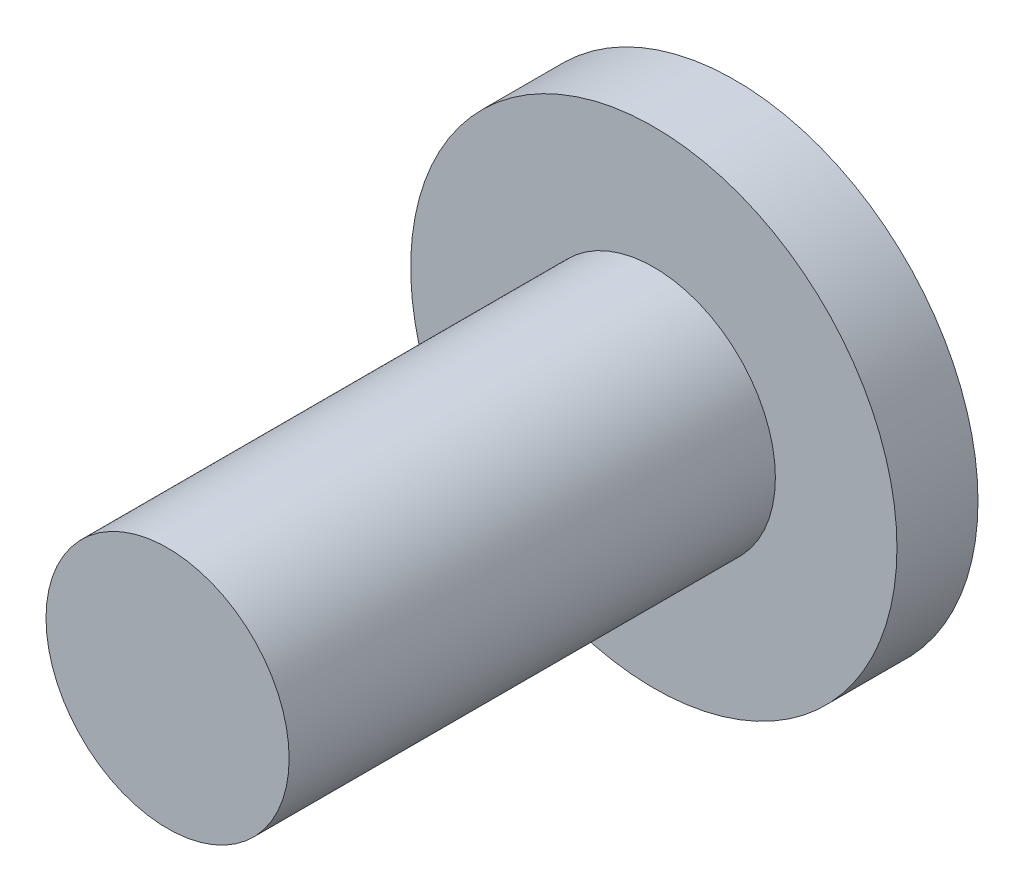
SolidWorks part; units mm, degrees
ref_plane "前视基准面" through (0, 0, 0) normal (0, 0, 1) x (1, 0, 0)
ref_plane "上视基准面" through (0, 0, 0) normal (0, 1, 0) x (1, 0, 0)
ref_plane "右视基准面" through (0, 0, 0) normal (1, 0, 0) x (0, 0, -1)
other "Configuration Table"
sketch "草图1" plane through (0, 0, 0) normal (0, 0, 1) x (1, 0, 0)
  circle A0 centre (0, 0) radius 3
  dimension "D1" = 6
extrude "凸台-拉伸1" add sketch "草图1" along normal blind 1
sketch "草图2" plane through (0, 0, 0) normal (0, 0, -1) x (-1, 0, 0)
  line L1 (1.1547, 0) -> (0.5774, 1)
  line L2 (0.5774, 1) -> (-0.5774, 1)
  line L3 (-0.5774, 1) -> (-1.1547, 0)
  line L4 (-1.1547, 0) -> (-0.5774, -1)
  line L5 (-0.5774, -1) -> (0.5774, -1)
  line L6 (0.5774, -1) -> (1.1547, 0)
  circle A0 centre (0, 0) radius 1 construction
  dimension "D1" = 2
extrude "切除-拉伸1" cut sketch "草图2" against normal blind 1
sketch "草图3" plane through (0, 0, 1) normal (0, 0, 1) x (1, 0, 0)
  circle A0 centre (0, 0) radius 1.5
  dimension "D1" = 3
extrude "凸台-拉伸2" add sketch "草图3" along normal blind 6
